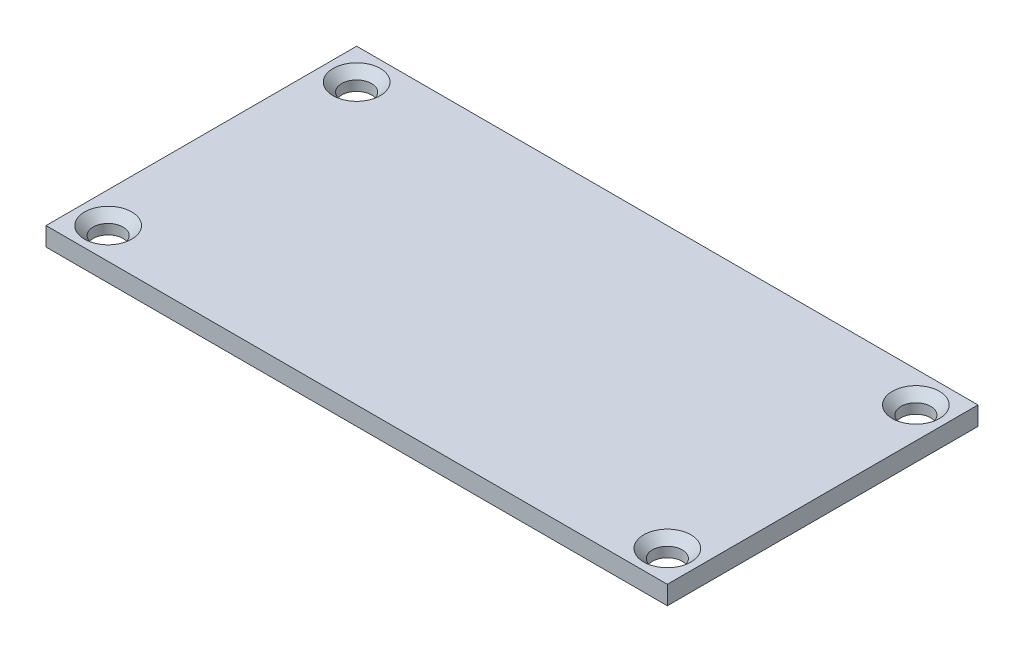
SolidWorks part; units mm, degrees
ref_plane "前视基准面" through (0, 0, 0) normal (0, 0, 1) x (1, 0, 0)
ref_plane "上视基准面" through (0, 0, 0) normal (0, 1, 0) x (1, 0, 0)
ref_plane "右视基准面" through (0, 0, 0) normal (1, 0, 0) x (0, 0, -1)
sketch "草图1" plane through (0, 0, 0) normal (0, 1, 0) x (1, 0, 0)
  line L1 (0, 0) -> (50, 0)
  line L2 (0, 0) -> (0, 25)
  line L3 (0, 25) -> (50, 25)
  line L4 (50, 0) -> (50, 25)
  dimension "D1" = 50
  dimension "D2" = 25
extrude "凸台-拉伸1" add sketch "草图1" along normal blind 1.5
hole_wizard "M2 平头机械螺钉的锥形沉头孔1" positions "草图2" profile "草图3" countersink size "M2" standard "ANSI Metric"
sketch "草图2" plane through (0, 1.5, 0) normal (0, 1, 0) x (1, 0, 0)
  line L0 (0, 25) -> (0, 0) construction
  line L1 (50, 25) -> (0, 25) construction
  point P0 (2.5, 22.5)
  dimension "D1" = 2.5
  dimension "D2" = 2.5
sketch "草图3" plane through (2.5, 1.5, -22.5) normal (1, 0, 0) x (0, 0, 1)
  line L0 (0, 0) -> (0, 8.721)
  line L1 (0, 8.721) -> (1.2, 8)
  line L2 (1.2, 8) -> (1.2, 0.7)
  line L3 (1.2, 0.7) -> (1.9, 0)
  line L5 (1.9, 0) -> (0, 0)
  line L6 (-1.2, 0.7) -> (-1.9, 0) construction
  line L10 (0, 8.721) -> (-1.2, 8) construction
  line L11 (0, -6.35) -> (0, 107.95) construction
  dimension "孔直径" = 2.4
  dimension "孔深度" = 8
  dimension "近端锥形沉头孔直径" = 3.8
  dimension "近端锥形沉头孔角度" = 90
  dimension "导头角度" = 118
pattern_linear "阵列(线性)1" count 2 spacing 45 along (1, 0, 0) count 2 spacing 20 along (0, 0, 1) of "M2 平头机械螺钉的锥形沉头孔1"
